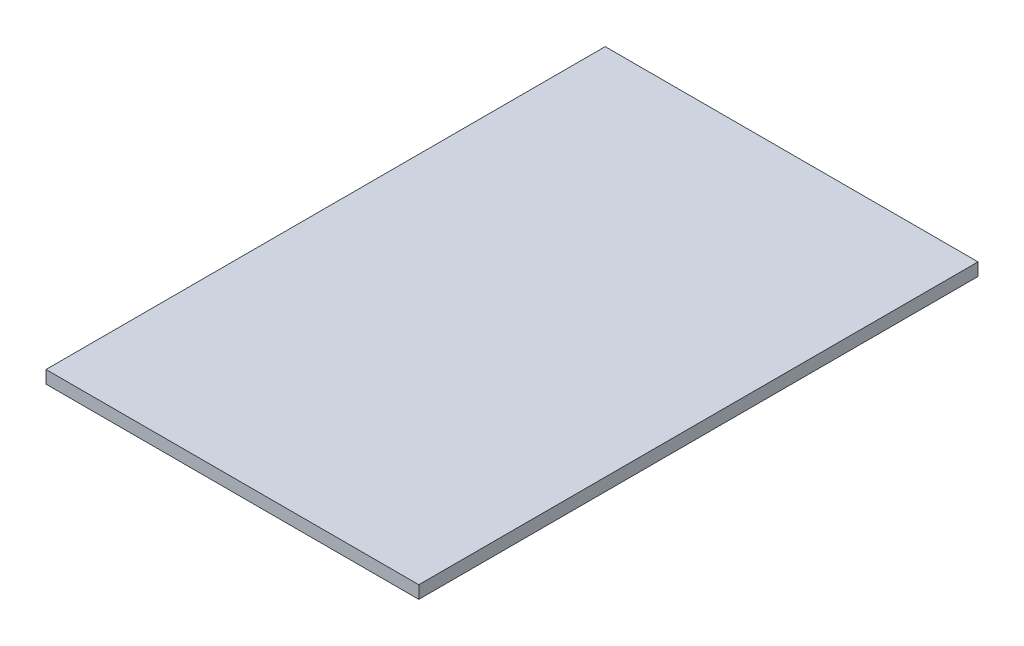
SolidWorks part; units mm, degrees
ref_plane "Front Plane" through (0, 0, 0) normal (0, 0, 1) x (1, 0, 0)
ref_plane "Top Plane" through (0, 0, 0) normal (0, 1, 0) x (1, 0, 0)
ref_plane "Right Plane" through (0, 0, 0) normal (1, 0, 0) x (0, 0, -1)
sketch "Sketch1" plane through (0, 0, 0) normal (0, 1, 0) x (1, 0, 0)
  line L0 (-97.5279, 759.6989) -> (-97.5279, -78.5011)
  line L1 (-97.5279, -78.5011) -> (461.2721, -78.5011)
  line L2 (-97.5279, 759.6989) -> (461.2721, 759.6989)
  line L3 (461.2721, -78.5011) -> (461.2721, 759.6989)
extrude "Boss-Extrude1" add sketch "Sketch1" along normal blind 19.05
